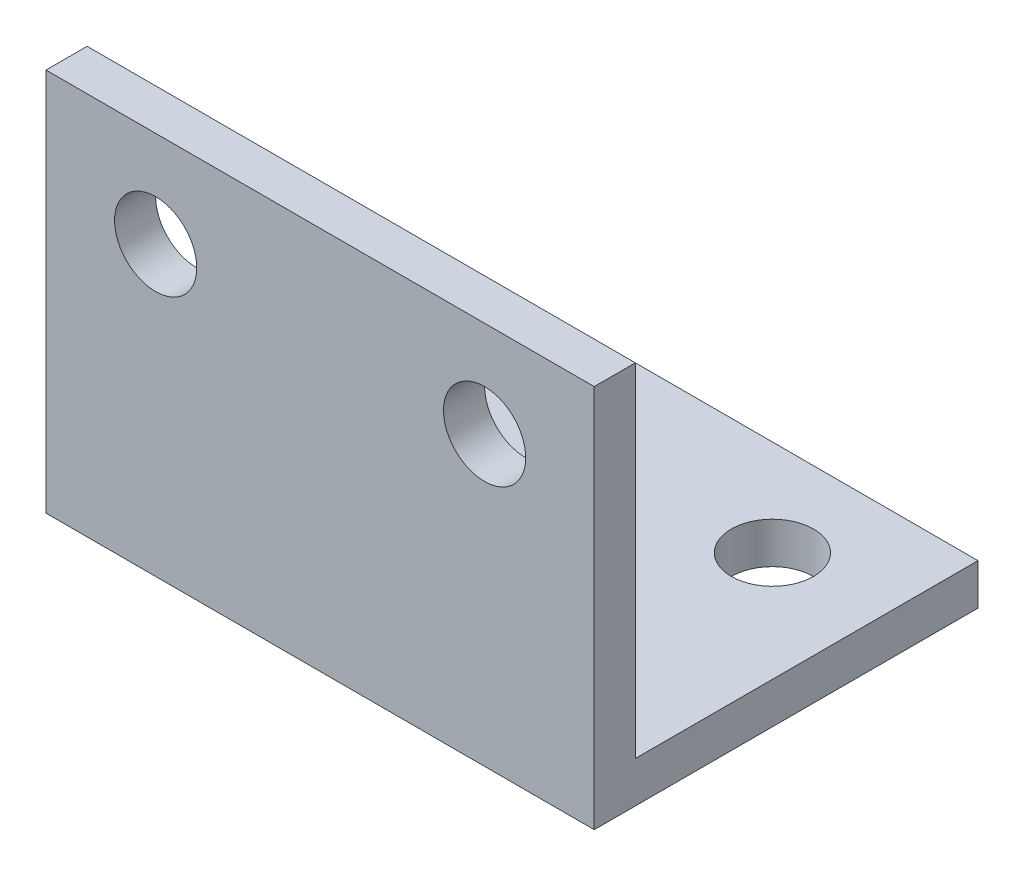
SolidWorks part; units mm, degrees
ref_plane "前视基准面" through (0, 0, 0) normal (0, 0, 1) x (1, 0, 0)
ref_plane "上视基准面" through (0, 0, 0) normal (0, 1, 0) x (1, 0, 0)
ref_plane "右视基准面" through (0, 0, 0) normal (1, 0, 0) x (0, 0, -1)
sketch "草图1" plane through (0, 0, 0) normal (1, 0, 0) x (0, 0, -1)
  line L0 (0, 0) -> (0, 14)
  line L1 (0, 14) -> (1.5, 14)
  line L2 (1.5, 14) -> (1.5, 1.5)
  line L3 (1.5, 1.5) -> (14, 1.5)
  line L4 (14, 1.5) -> (14, 0)
  line L5 (14, 0) -> (0, 0)
  dimension "D1" = 14
  dimension "D2" = 14
  dimension "D3" = 1.5
  dimension "D4" = 1.5
extrude "凸台-拉伸1" add sketch "草图1" along normal blind 20
sketch "草图2" plane through (0, 0, -1.5) normal (0, 0, -1) x (-1, 0, 0)
  line L0 (-10, 14) -> (-10, 1.5) construction
  line L1 (-20, 14) -> (0, 14) construction
  line L2 (-20, 1.5) -> (0, 1.5) construction
  line L3 (-20, 0) -> (0, 0) construction
  circle A0 centre (-16, 10.5) radius 1.5
  circle A1 centre (-4, 10.5) radius 1.5
  dimension "D1" = 3
  dimension "D2" = 12
  dimension "D3" = 6
  dimension "D4" = 10.5
extrude "切除-拉伸1" cut sketch "草图2" against normal through all
sketch "草图3" plane through (0, 1.5, 0) normal (0, 1, 0) x (1, 0, 0)
  line L0 (10, 14) -> (10, 1.5) construction
  line L1 (20, 14) -> (0, 14) construction
  line L2 (20, 1.5) -> (0, 1.5) construction
  line L3 (20, 0) -> (0, 0) construction
  circle A0 centre (4, 10.5) radius 1.5
  circle A1 centre (16, 10.5) radius 1.5
  dimension "D2" = 3
  dimension "D1" = 12
  dimension "D3" = 6
  dimension "D4" = 10.5
extrude "切除-拉伸2" cut sketch "草图3" against normal through all
